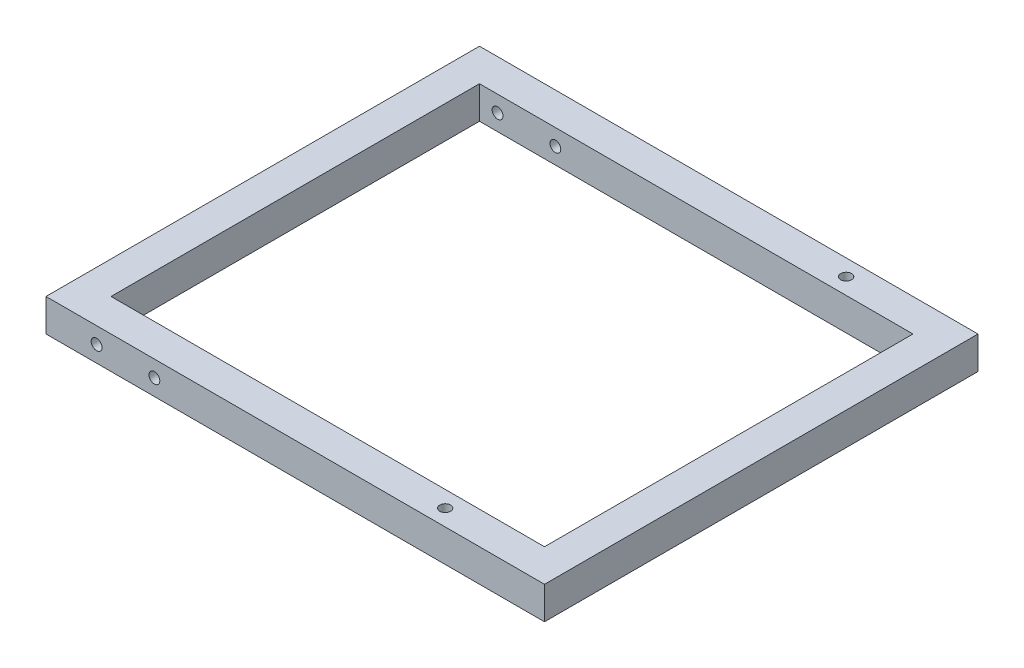
SolidWorks part; units mm, degrees
ref_plane "Front Plane" through (0, 0, 0) normal (0, 0, 1) x (1, 0, 0)
ref_plane "Top Plane" through (0, 0, 0) normal (0, 1, 0) x (1, 0, 0)
ref_plane "Right Plane" through (0, 0, 0) normal (1, 0, 0) x (0, 0, -1)
sketch "Sketch1" plane through (0, 0, 0) normal (0, 1, 0) x (1, 0, 0)
  line L1 (0, 0) -> (438.15, 0)
  line L2 (0, 0) -> (0, -381)
  line L3 (0, -381) -> (438.15, -381)
  line L4 (438.15, 0) -> (438.15, -381)
  line L5 (28.575, -28.575) -> (409.575, -28.575)
  line L6 (28.575, -28.575) -> (28.575, -352.425)
  line L7 (28.575, -352.425) -> (409.575, -352.425)
  line L8 (409.575, -28.575) -> (409.575, -352.425)
  dimension "D1" = 438.15
  dimension "D2" = 381
  dimension "D3" = 28.575
  dimension "D4" = 28.575
  dimension "D5" = 28.575
  dimension "D6" = 28.575
extrude "Boss-Extrude1" add sketch "Sketch1" along normal blind 28.575
sketch "Sketch2" plane through (0, 0, 0) normal (0, 0, -1) x (-1, 0, 0)
  line L0 (0, 28.575) -> (0, 0) construction
  circle A0 centre (-44.45, 14.2875) radius 4.7625
  circle A1 centre (-95.25, 14.2875) radius 4.7625
  point P4 (0, 14.2875)
  dimension "D2" = 9.525
  dimension "D3" = 50.8
  dimension "D4" = 9.525
  dimension "D1" = 44.45
extrude "Cut-Extrude1" cut sketch "Sketch2" against normal through all
sketch "Sketch3" plane through (0, 28.575, 0) normal (0, 1, 0) x (1, 0, 0)
  line L0 (438.15, -381) -> (438.15, 0) construction
  line L3 (438.15, 0) -> (0, 0) construction
  line L4 (0, -190.5) -> (438.15, -190.5) construction
  line L5 (0, 0) -> (0, -381) construction
  circle A0 centre (336.55, -14.2875) radius 4.7625
  circle A1 centre (336.55, -366.7125) radius 4.7625
  dimension "D3" = 9.525
  dimension "D1" = 101.6
  dimension "D2" = 14.2875
extrude "Cut-Extrude2" cut sketch "Sketch3" against normal blind 28.575
